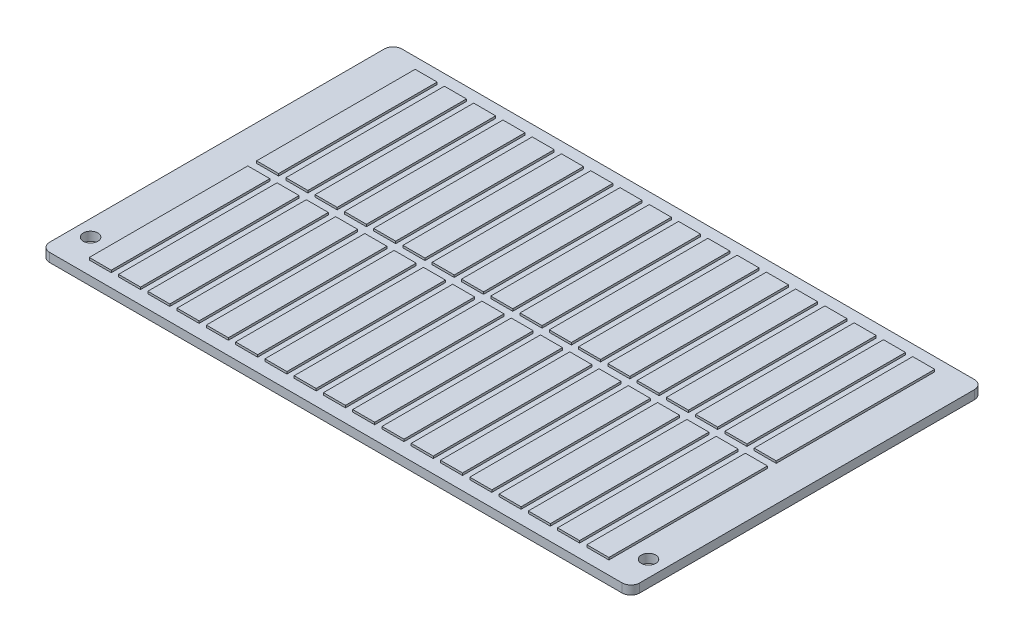
SolidWorks part; units mm, degrees
ref_plane "Alzado" through (0, 0, 0) normal (0, 0, 1) x (1, 0, 0)
ref_plane "Planta" through (0, 0, 0) normal (0, 1, 0) x (1, 0, 0)
ref_plane "Vista lateral" through (0, 0, 0) normal (1, 0, 0) x (0, 0, -1)
sketch "Croquis1" plane through (0, 0, 0) normal (0, 1, 0) x (1, 0, 0)
  line L1 (170.18, -101.6) -> (-170.18, -101.6)
  line L2 (170.18, -101.6) -> (170.18, 101.6)
  line L3 (170.18, 101.6) -> (-170.18, 101.6)
  line L4 (-170.18, -101.6) -> (-170.18, 101.6)
  line L5 (170.18, -101.6) -> (-170.18, 101.6) construction
  line L6 (170.18, 101.6) -> (-170.18, -101.6) construction
  point P0 (0, 0)
  dimension "D1" = 203.2
  dimension "D2" = 340.36
extrude "Saliente-Extruir1" add sketch "Croquis1" along normal blind 5.08
sketch "Croquis2" plane through (0, 5.08, 0) normal (0, 1, 0) x (1, 0, 0)
  line L0 (-170.18, 101.6) -> (-170.18, -101.6) construction
  line L5 (-149.86, 93.98) -> (-137.16, 93.98)
  line L6 (-149.86, 93.98) -> (-149.86, 2.54)
  line L7 (-149.86, 2.54) -> (-137.16, 2.54)
  line L8 (-137.16, 93.98) -> (-137.16, 2.54)
  line L9 (170.18, 101.6) -> (-170.18, 101.6) construction
  line L10 (-132.9765, 93.98) -> (-132.9765, 2.54)
  line L11 (-132.9765, 93.98) -> (-120.2765, 93.98)
  line L12 (-120.2765, 93.98) -> (-120.2765, 2.54)
  line L13 (-132.9765, 2.54) -> (-120.2765, 2.54)
  line L14 (-116.0929, 93.98) -> (-116.0929, 2.54)
  line L15 (-116.0929, 93.98) -> (-103.3929, 93.98)
  line L16 (-103.3929, 93.98) -> (-103.3929, 2.54)
  line L17 (-116.0929, 2.54) -> (-103.3929, 2.54)
  line L18 (-99.2094, 93.98) -> (-99.2094, 2.54)
  line L19 (-99.2094, 93.98) -> (-86.5094, 93.98)
  line L20 (-86.5094, 93.98) -> (-86.5094, 2.54)
  line L21 (-99.2094, 2.54) -> (-86.5094, 2.54)
  line L22 (-82.3259, 93.98) -> (-82.3259, 2.54)
  line L23 (-82.3259, 93.98) -> (-69.6259, 93.98)
  line L24 (-69.6259, 93.98) -> (-69.6259, 2.54)
  line L25 (-82.3259, 2.54) -> (-69.6259, 2.54)
  line L26 (-65.4424, 93.98) -> (-65.4424, 2.54)
  line L27 (-65.4424, 93.98) -> (-52.7424, 93.98)
  line L28 (-52.7424, 93.98) -> (-52.7424, 2.54)
  line L29 (-65.4424, 2.54) -> (-52.7424, 2.54)
  line L30 (-48.5588, 93.98) -> (-48.5588, 2.54)
  line L31 (-48.5588, 93.98) -> (-35.8588, 93.98)
  line L32 (-35.8588, 93.98) -> (-35.8588, 2.54)
  line L33 (-48.5588, 2.54) -> (-35.8588, 2.54)
  line L34 (-31.6753, 93.98) -> (-31.6753, 2.54)
  line L35 (-31.6753, 93.98) -> (-18.9753, 93.98)
  line L36 (-18.9753, 93.98) -> (-18.9753, 2.54)
  line L37 (-31.6753, 2.54) -> (-18.9753, 2.54)
  line L38 (-14.7918, 93.98) -> (-14.7918, 2.54)
  line L39 (-14.7918, 93.98) -> (-2.0918, 93.98)
  line L40 (-2.0918, 93.98) -> (-2.0918, 2.54)
  line L41 (-14.7918, 2.54) -> (-2.0918, 2.54)
  line L42 (2.0918, 93.98) -> (2.0918, 2.54)
  line L43 (2.0918, 93.98) -> (14.7918, 93.98)
  line L44 (14.7918, 93.98) -> (14.7918, 2.54)
  line L45 (2.0918, 2.54) -> (14.7918, 2.54)
  line L46 (18.9753, 93.98) -> (18.9753, 2.54)
  line L47 (18.9753, 93.98) -> (31.6753, 93.98)
  line L48 (31.6753, 93.98) -> (31.6753, 2.54)
  line L49 (18.9753, 2.54) -> (31.6753, 2.54)
  line L50 (35.8588, 93.98) -> (35.8588, 2.54)
  line L51 (35.8588, 93.98) -> (48.5588, 93.98)
  line L52 (48.5588, 93.98) -> (48.5588, 2.54)
  line L53 (35.8588, 2.54) -> (48.5588, 2.54)
  line L54 (52.7424, 93.98) -> (52.7424, 2.54)
  line L55 (52.7424, 93.98) -> (65.4424, 93.98)
  line L56 (65.4424, 93.98) -> (65.4424, 2.54)
  line L57 (52.7424, 2.54) -> (65.4424, 2.54)
  line L58 (69.6259, 93.98) -> (69.6259, 2.54)
  line L59 (69.6259, 93.98) -> (82.3259, 93.98)
  line L60 (82.3259, 93.98) -> (82.3259, 2.54)
  line L61 (69.6259, 2.54) -> (82.3259, 2.54)
  line L62 (86.5094, 93.98) -> (86.5094, 2.54)
  line L63 (86.5094, 93.98) -> (99.2094, 93.98)
  line L64 (99.2094, 93.98) -> (99.2094, 2.54)
  line L65 (86.5094, 2.54) -> (99.2094, 2.54)
  line L66 (103.3929, 93.98) -> (103.3929, 2.54)
  line L67 (103.3929, 93.98) -> (116.0929, 93.98)
  line L68 (116.0929, 93.98) -> (116.0929, 2.54)
  line L69 (103.3929, 2.54) -> (116.0929, 2.54)
  line L70 (120.2765, 93.98) -> (120.2765, 2.54)
  line L71 (120.2765, 93.98) -> (132.9765, 93.98)
  line L72 (132.9765, 93.98) -> (132.9765, 2.54)
  line L73 (120.2765, 2.54) -> (132.9765, 2.54)
  line L74 (137.16, 93.98) -> (137.16, 2.54)
  line L75 (137.16, 93.98) -> (149.86, 93.98)
  line L76 (149.86, 93.98) -> (149.86, 2.54)
  line L77 (137.16, 2.54) -> (149.86, 2.54)
  line L78 (170.18, -101.6) -> (170.18, 101.6) construction
  line L79 (0, 0) -> (-170.18, 0) construction
  line L80 (137.16, -93.98) -> (149.86, -93.98)
  line L81 (149.86, -93.98) -> (149.86, -2.54)
  line L82 (137.16, -2.54) -> (149.86, -2.54)
  line L83 (137.16, -93.98) -> (137.16, -2.54)
  line L84 (120.2765, -93.98) -> (132.9765, -93.98)
  line L85 (132.9765, -93.98) -> (132.9765, -2.54)
  line L86 (120.2765, -2.54) -> (132.9765, -2.54)
  line L87 (120.2765, -93.98) -> (120.2765, -2.54)
  line L88 (103.3929, -93.98) -> (116.0929, -93.98)
  line L89 (116.0929, -93.98) -> (116.0929, -2.54)
  line L90 (103.3929, -2.54) -> (116.0929, -2.54)
  line L91 (103.3929, -93.98) -> (103.3929, -2.54)
  line L92 (86.5094, -93.98) -> (99.2094, -93.98)
  line L93 (99.2094, -93.98) -> (99.2094, -2.54)
  line L94 (86.5094, -2.54) -> (99.2094, -2.54)
  line L95 (86.5094, -93.98) -> (86.5094, -2.54)
  line L96 (69.6259, -93.98) -> (82.3259, -93.98)
  line L97 (82.3259, -93.98) -> (82.3259, -2.54)
  line L98 (69.6259, -2.54) -> (82.3259, -2.54)
  line L99 (69.6259, -93.98) -> (69.6259, -2.54)
  line L100 (52.7424, -93.98) -> (65.4424, -93.98)
  line L101 (65.4424, -93.98) -> (65.4424, -2.54)
  line L102 (52.7424, -2.54) -> (65.4424, -2.54)
  line L103 (52.7424, -93.98) -> (52.7424, -2.54)
  line L104 (35.8588, -93.98) -> (48.5588, -93.98)
  line L105 (48.5588, -93.98) -> (48.5588, -2.54)
  line L106 (35.8588, -2.54) -> (48.5588, -2.54)
  line L107 (35.8588, -93.98) -> (35.8588, -2.54)
  line L108 (18.9753, -93.98) -> (31.6753, -93.98)
  line L109 (31.6753, -93.98) -> (31.6753, -2.54)
  line L110 (18.9753, -2.54) -> (31.6753, -2.54)
  line L111 (18.9753, -93.98) -> (18.9753, -2.54)
  line L112 (2.0918, -93.98) -> (14.7918, -93.98)
  line L113 (14.7918, -93.98) -> (14.7918, -2.54)
  line L114 (2.0918, -2.54) -> (14.7918, -2.54)
  line L115 (2.0918, -93.98) -> (2.0918, -2.54)
  line L116 (-14.7918, -93.98) -> (-2.0918, -93.98)
  line L117 (-2.0918, -93.98) -> (-2.0918, -2.54)
  line L118 (-14.7918, -2.54) -> (-2.0918, -2.54)
  line L119 (-14.7918, -93.98) -> (-14.7918, -2.54)
  line L120 (-31.6753, -93.98) -> (-18.9753, -93.98)
  line L121 (-18.9753, -93.98) -> (-18.9753, -2.54)
  line L122 (-31.6753, -2.54) -> (-18.9753, -2.54)
  line L123 (-31.6753, -93.98) -> (-31.6753, -2.54)
  line L124 (-48.5588, -93.98) -> (-35.8588, -93.98)
  line L125 (-35.8588, -93.98) -> (-35.8588, -2.54)
  line L126 (-48.5588, -2.54) -> (-35.8588, -2.54)
  line L127 (-48.5588, -93.98) -> (-48.5588, -2.54)
  line L128 (-65.4424, -93.98) -> (-52.7424, -93.98)
  line L129 (-52.7424, -93.98) -> (-52.7424, -2.54)
  line L130 (-65.4424, -2.54) -> (-52.7424, -2.54)
  line L131 (-65.4424, -93.98) -> (-65.4424, -2.54)
  line L132 (-82.3259, -93.98) -> (-69.6259, -93.98)
  line L133 (-69.6259, -93.98) -> (-69.6259, -2.54)
  line L134 (-82.3259, -2.54) -> (-69.6259, -2.54)
  line L135 (-82.3259, -93.98) -> (-82.3259, -2.54)
  line L136 (-99.2094, -93.98) -> (-86.5094, -93.98)
  line L137 (-86.5094, -93.98) -> (-86.5094, -2.54)
  line L138 (-99.2094, -2.54) -> (-86.5094, -2.54)
  line L139 (-99.2094, -93.98) -> (-99.2094, -2.54)
  line L140 (-116.0929, -93.98) -> (-103.3929, -93.98)
  line L141 (-103.3929, -93.98) -> (-103.3929, -2.54)
  line L142 (-116.0929, -2.54) -> (-103.3929, -2.54)
  line L143 (-116.0929, -93.98) -> (-116.0929, -2.54)
  line L144 (-132.9765, -93.98) -> (-120.2765, -93.98)
  line L145 (-120.2765, -93.98) -> (-120.2765, -2.54)
  line L146 (-132.9765, -2.54) -> (-120.2765, -2.54)
  line L147 (-132.9765, -93.98) -> (-132.9765, -2.54)
  line L148 (-149.86, -2.54) -> (-137.16, -2.54)
  line L149 (-137.16, -93.98) -> (-137.16, -2.54)
  line L150 (-149.86, -93.98) -> (-137.16, -93.98)
  line L151 (-149.86, -93.98) -> (-149.86, -2.54)
  dimension "D1" = 20.32
  dimension "D2" = 7.62
  dimension "D3" = 12.7
  dimension "D4" = 2.54
  dimension "D6" = 20.32
  dimension "D5" = 18
extrude "Saliente-Extruir2" add sketch "Croquis2" along normal blind 1.27
sketch "Croquis3" plane through (0, 5.08, 0) normal (0, 1, 0) x (1, 0, 0)
  line L2 (-170.18, -101.6) -> (170.18, -101.6) construction
  line L3 (-160.909, -82.169) -> (-160.909, -86.36) construction
  line L4 (-160.909, -82.169) -> (-165.1, -82.169) construction
  line L5 (-170.18, 101.6) -> (-170.18, -101.6) construction
  line L6 (160.909, -82.169) -> (160.909, -86.36) construction
  line L7 (160.909, -86.36) -> (160.909, -82.169) construction
  line L8 (160.909, -82.169) -> (165.1, -82.169) construction
  line L9 (170.18, -101.6) -> (170.18, 101.6) construction
  circle A0 centre (-160.909, -82.169) radius 4.191
  circle A1 centre (160.909, -82.169) radius 4.191
  dimension "D1" = 8.382
  dimension "D2" = 8.382
  dimension "D3" = 5.08
  dimension "D4" = 5.08
  dimension "D5" = 15.24
  dimension "D6" = 15.24
extrude "Cortar-Extruir1" cut sketch "Croquis3" against normal blind 10
fillet "Redondeo1" radius 5.08 4 edges at (170.18, 2.54, -101.6) (-170.18, 2.54, -101.6) (170.18, 2.54, 101.6) (-170.18, 2.54, 101.6)
